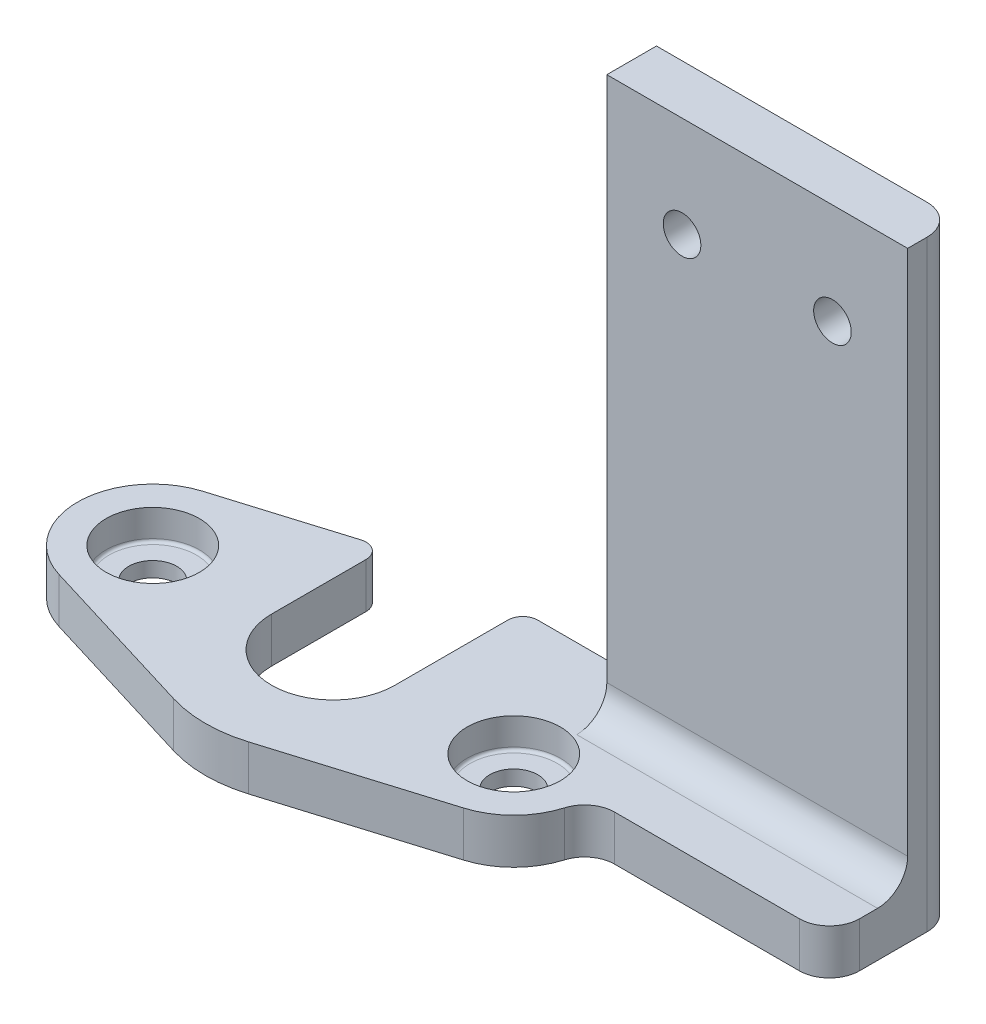
SolidWorks part; units mm, degrees
ref_plane "Спереди" through (0, 0, 0) normal (0, 0, 1) x (1, 0, 0)
ref_plane "Сверху" through (0, 0, 0) normal (0, 1, 0) x (1, 0, 0)
ref_plane "Справа" through (0, 0, 0) normal (1, 0, 0) x (0, 0, -1)
sketch "Эскиз1" plane through (0, -18, 0) normal (0, 1, 0) x (1, 0, 0)
  line L5 (9.5208, 86.7315) -> (-1.4583, 90.0793)
  line L6 (14.4792, 86.7315) -> (25.4583, 90.0793)
  line L8 (-1.4583, 99.6445) -> (6.6083, 102.1042)
  line L9 (7.9, 94.8619) -> (7.9, 101.1477)
  line L10 (16.1, 94.8619) -> (16.1, 102.3619)
  line L11 (17.1, 103.3619) -> (44.9886, 103.3619)
  line L16 (44.9886, 103.3619) -> (44.9886, 94.8619)
  line L19 (29, 94.8619) -> (44.9886, 94.8619)
  arc A7 (7.9, 94.8619) -> (16.1, 94.8619) centre (12, 94.8619) ccw
  circle A8 centre (24, 94.8619) radius 1.6
  circle A9 centre (0, 94.8619) radius 1.6
  arc A10 (-1.4583, 99.6445) -> (-1.4583, 90.0793) centre (0, 94.8619) ccw
  arc A12 (9.5208, 86.7315) -> (14.4792, 86.7315) centre (12, 94.8619) ccw
  arc A14 (25.4583, 90.0793) -> (29, 94.8619) centre (24, 94.8619) ccw
  arc A15 (17.1, 103.3619) -> (16.1, 102.3619) centre (17.1, 102.3619) ccw
  arc A16 (6.6083, 102.1042) -> (7.9, 101.1477) centre (6.9, 101.1477) cw
  dimension "D1" = 1
extrude "Бобышка-Вытянуть1" add sketch "Эскиз1" along normal blind 3
sketch "Эскиз2" plane through (0, -15, 0) normal (0, 1, 0) x (1, 0, 0)
  circle A0 centre (0, 94.8619) radius 3.1
  circle A2 centre (24, 94.8619) radius 3.1
extrude "Вырез-Вытянуть1" cut sketch "Эскиз2" against normal blind 2
fillet "Скругление1" radius 0.2 2 edges at (24, -17, -91.7619) (0, -17, -91.7619)
sketch "Эскиз4" plane through (0, -15, 0) normal (0, 1, 0) x (1, 0, 0)
  line L5 (24.9886, 100.0619) -> (44.9886, 100.0619)
  line L6 (24.9886, 100.0619) -> (24.9886, 103.3619)
  line L7 (24.9886, 103.3619) -> (44.9886, 103.3619)
  line L8 (44.9886, 100.0619) -> (44.9886, 103.3619)
extrude "Бобышка-Вытянуть2" add sketch "Эскиз4" along normal up to surface (37 mm away)
fillet "Скругление2" radius 2 4 edges at (34.9886, -15, -100.0619) (44.9886, 2, -103.3619) (29, -16.5, -94.8619) (44.9886, -16.5, -94.8619)
sketch "Эскиз5" plane through (0, 0, -100.0619) normal (0, 0, 1) x (1, 0, 0)
  circle A0 centre (39.9886, 15.3) radius 1.25
  circle A1 centre (29.9886, 15.3) radius 1.25
extrude "Вырез-Вытянуть2" cut sketch "Эскиз5" against normal up to surface (3.3 mm away) up to face at (28.3591, -3.6667, -103.3619)
